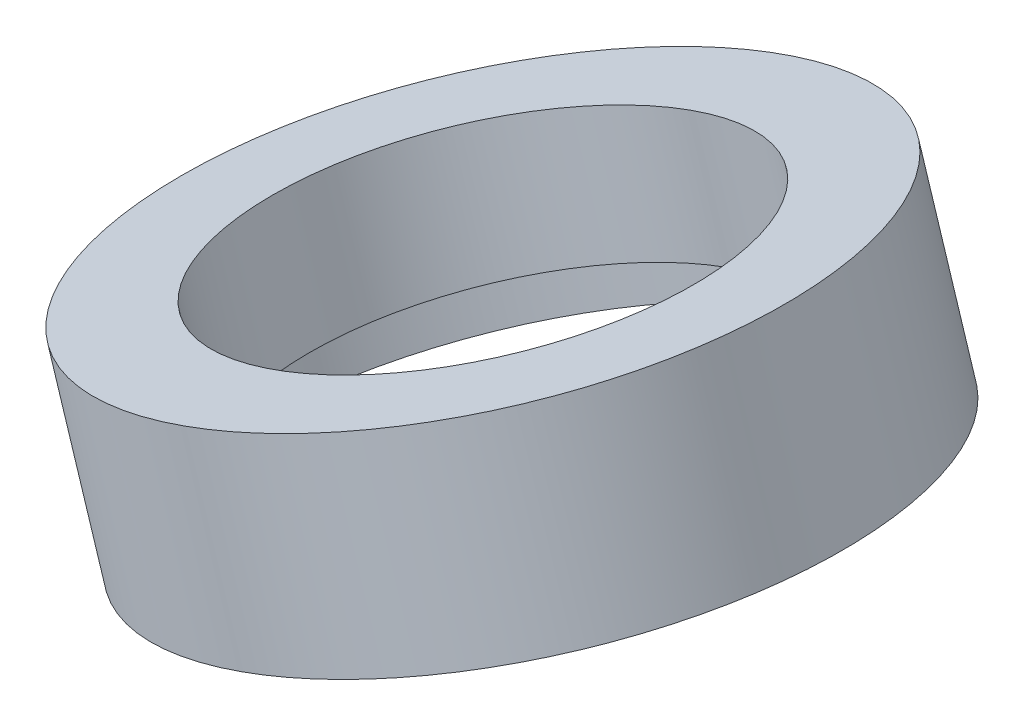
SolidWorks part; units mm, degrees
material "6061-T6 (SS)"
ref_plane "Alzado" through (0, 0, 0) normal (0, 0, 1) x (1, 0, 0)
ref_plane "Planta" through (0, 0, 0) normal (0, 1, 0) x (1, 0, 0)
ref_plane "Vista lateral" through (0, 0, 0) normal (1, 0, 0) x (0, 0, -1)
sketch "Sk_Cazoleta" plane through (0, 0, 0) normal (0, 0, 1) x (1, 0, 0)
  line L0 (373.4203, 555.0431) -> (379.3333, 556.9075)
  line L1 (379.3333, 556.9075) -> (383.0922, 544.9861)
  line L2 (383.0922, 544.9861) -> (382.2339, 544.7154)
  line L3 (382.2339, 544.7154) -> (380.8807, 549.0071)
  line L4 (380.8807, 549.0071) -> (375.826, 547.4134)
  line L5 (375.826, 547.4134) -> (373.4203, 555.0431)
  line L6 (358.2786, 555.5114) -> (368.8036, 522.1314) construction
revolve "Cazoleta" add sketch "Sk_Cazoleta" angle 360 about L6
